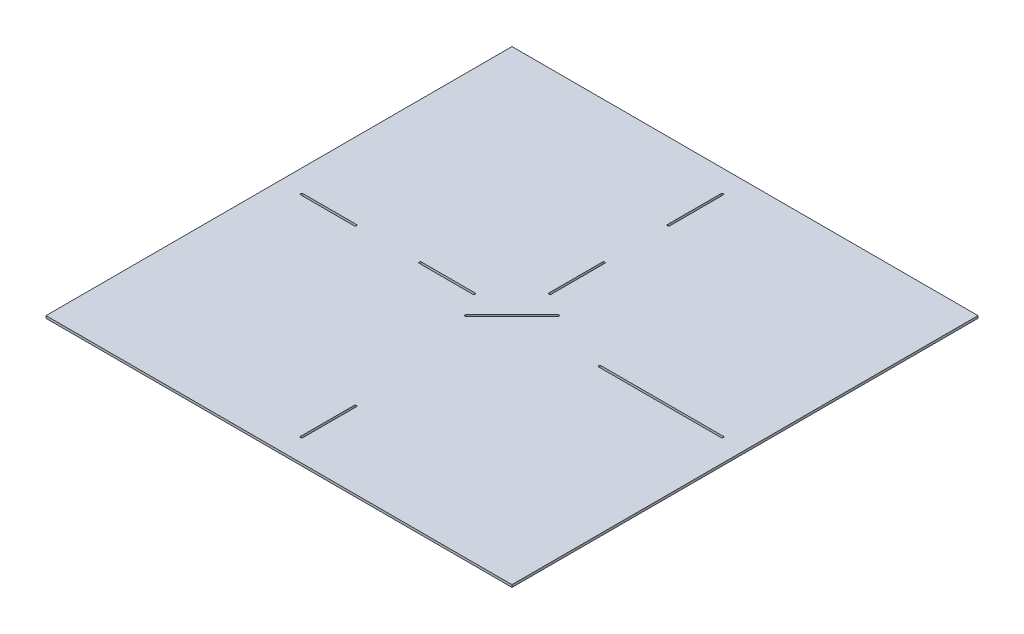
SolidWorks part; units mm, degrees
ref_plane "Front Plane" through (0, 0, 0) normal (0, 0, 1) x (1, 0, 0)
ref_plane "Top Plane" through (0, 0, 0) normal (0, 1, 0) x (1, 0, 0)
ref_plane "Right Plane" through (0, 0, 0) normal (1, 0, 0) x (0, 0, -1)
sketch "Sketch1" plane through (0, 0, 0) normal (0, 1, 0) x (1, 0, 0)
  line L1 (-304.8, -304.8) -> (304.8, -304.8)
  line L2 (-304.8, -304.8) -> (-304.8, 304.8)
  line L3 (-304.8, 304.8) -> (304.8, 304.8)
  line L4 (304.8, -304.8) -> (304.8, 304.8)
  line L5 (-304.8, -304.8) -> (304.8, 304.8) construction
  line L6 (-304.8, 304.8) -> (304.8, -304.8) construction
  point P0 (0, 0)
  dimension "D1" = 609.6
  dimension "D2" = 609.6
extrude "Boss-Extrude1" add sketch "Sketch1" along normal blind 3.175
sketch "Sketch3" plane through (0, 3.175, 0) normal (0, 1, 0) x (1, 0, 0)
  line L0 (-30, -30) -> (30, 30) construction
  line L1 (-30, 30) -> (30, 30) construction
  line L2 (-30, 30) -> (-30, -30) construction
  line L3 (-30, -30) -> (30, -30) construction
  line L4 (30, 30) -> (30, -30) construction
  line L5 (-30, 30) -> (30, -30) construction
  line L6 (-30, -30) -> (30, 30) construction
  line L7 (-31.0607, -28.9393) -> (28.9393, 31.0607)
  line L8 (-28.9393, -31.0607) -> (31.0607, 28.9393)
  arc A0 (-31.0607, -28.9393) -> (-28.9393, -31.0607) centre (-30, -30) ccw
  arc A1 (31.0607, 28.9393) -> (28.9393, 31.0607) centre (30, 30) ccw
  point P0 (0, 0)
  point P6 (0, 0)
  dimension "D1" = 60
  dimension "D2" = 60
  dimension "D3" = 1.5
extrude "Cut-Extrude2" cut sketch "Sketch3" against normal through all
sketch "Sketch4" plane through (0, 3.175, 0) normal (0, 1, 0) x (1, 0, 0)
  line L0 (304.8, 0) -> (-304.8, 0) construction
  line L1 (304.8, -304.8) -> (304.8, 304.8) construction
  line L2 (-304.8, 304.8) -> (-304.8, -304.8) construction
  line L3 (0, -304.8) -> (0, 304.8) construction
  line L4 (-304.8, -304.8) -> (304.8, -304.8) construction
  line L5 (304.8, 304.8) -> (-304.8, 304.8) construction
  line L6 (-50, 0) -> (-120, 0) construction
  line L7 (275, 275) -> (-275, 275) construction
  line L8 (275, 275) -> (275, -275) construction
  line L9 (275, -275) -> (-275, -275) construction
  line L10 (-275, 275) -> (-275, -275) construction
  line L11 (275, 275) -> (-275, -275) construction
  line L12 (275, -275) -> (-275, 275) construction
  line L13 (50, 50) -> (-50, 50) construction
  line L14 (50, 50) -> (50, -50) construction
  line L15 (50, -50) -> (-50, -50) construction
  line L16 (-50, 50) -> (-50, -50) construction
  line L17 (50, 50) -> (-50, -50) construction
  line L18 (50, -50) -> (-50, 50) construction
  line L19 (-50, -1.5) -> (-120, -1.5)
  line L20 (-50, 1.5) -> (-120, 1.5)
  line L21 (0, 50) -> (0, 120) construction
  line L22 (-1.5, 50) -> (-1.5, 120)
  line L23 (1.5, 50) -> (1.5, 120)
  line L24 (0, -275) -> (0, -205) construction
  line L25 (-1.5, -275) -> (-1.5, -205)
  line L26 (1.5, -275) -> (1.5, -205)
  line L27 (275, 0) -> (115, 0) construction
  line L28 (275, -1.5) -> (115, -1.5)
  line L29 (275, 1.5) -> (115, 1.5)
  line L30 (-275, 0) -> (-205, 0) construction
  line L31 (-275, 1.5) -> (-205, 1.5)
  line L32 (-275, -1.5) -> (-205, -1.5)
  line L33 (0, 275) -> (0, 205) construction
  line L34 (1.5, 275) -> (1.5, 205)
  line L35 (-1.5, 275) -> (-1.5, 205)
  arc A0 (-50, -1.5) -> (-50, 1.5) centre (-50, 0) ccw
  arc A1 (-120, 1.5) -> (-120, -1.5) centre (-120, 0) ccw
  arc A2 (-1.5, 50) -> (1.5, 50) centre (0, 50) ccw
  arc A3 (1.5, 120) -> (-1.5, 120) centre (0, 120) ccw
  arc A4 (-1.5, -275) -> (1.5, -275) centre (0, -275) ccw
  arc A5 (1.5, -205) -> (-1.5, -205) centre (0, -205) ccw
  arc A6 (275, -1.5) -> (275, 1.5) centre (275, 0) ccw
  arc A7 (115, 1.5) -> (115, -1.5) centre (115, 0) ccw
  arc A8 (-275, 1.5) -> (-275, -1.5) centre (-275, 0) ccw
  arc A9 (-205, -1.5) -> (-205, 1.5) centre (-205, 0) ccw
  arc A10 (1.5, 275) -> (-1.5, 275) centre (0, 275) ccw
  arc A11 (-1.5, 205) -> (1.5, 205) centre (0, 205) ccw
  point P12 (0, 0)
  point P18 (0, 0)
  point P25 (-85, 0)
  point P32 (0, 85)
  point P39 (0, -240)
  point P46 (195, 0)
  point P53 (-240, 0)
  point P60 (0, 240)
  dimension "D1" = 550
  dimension "D2" = 550
  dimension "D3" = 100
  dimension "D4" = 100
extrude "Cut-Extrude3" cut sketch "Sketch4" against normal through all
